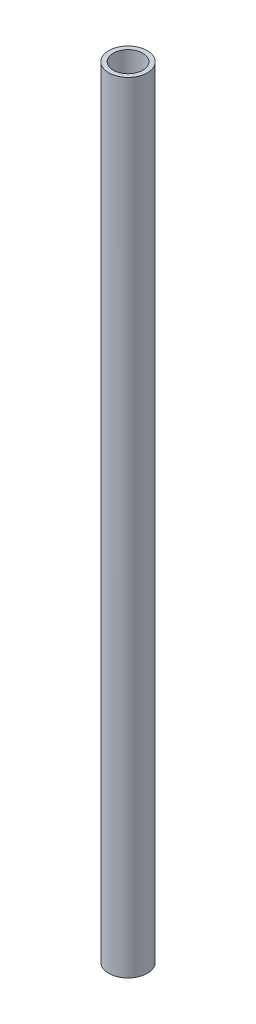
SolidWorks part; units mm, degrees
material "AISI 4130 Steel, normalized at 870C"
ref_plane "X-Y Datum" through (0, 0, 0) normal (0, 0, 1) x (1, 0, 0)
ref_plane "X-Z Datum" through (0, 0, 0) normal (0, 1, 0) x (1, 0, 0)
ref_plane "Y-Z Datum" through (0, 0, 0) normal (1, 0, 0) x (0, 0, -1)
sketch "Sketch1" plane through (0, 0, 0) normal (0, 1, 0) x (1, 0, 0)
  circle A0 centre (0, 0) radius 6.35
  circle A1 centre (0, 0) radius 4.8768
  dimension "D1" = 12.7
  dimension "D2" = 1.4732
extrude "Boss-Extrude1" add sketch "Sketch1" along normal up to body (128.58 mm away) from surface at -128.58 separate body
